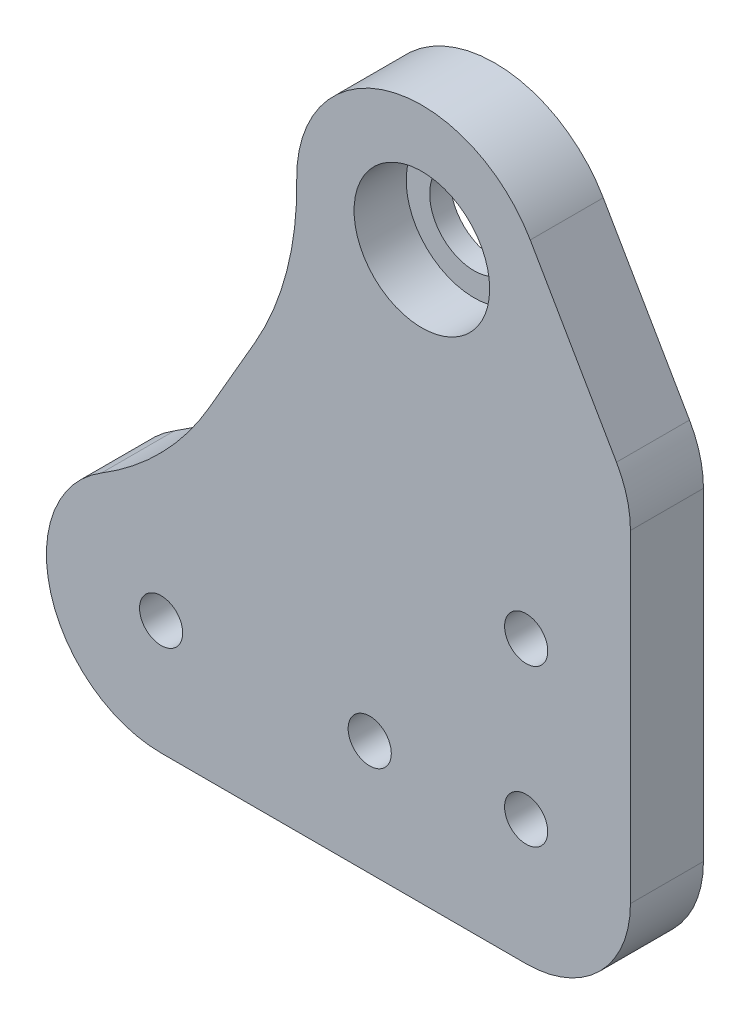
SolidWorks part; units mm, degrees
ref_plane "前视基准面" through (0, 0, 0) normal (0, 0, 1) x (1, 0, 0)
ref_plane "上视基准面" through (0, 0, 0) normal (0, 1, 0) x (1, 0, 0)
ref_plane "右视基准面" through (0, 0, 0) normal (1, 0, 0) x (0, 0, -1)
sketch "草图1" plane through (0, 0, 0) normal (0, 0, 1) x (1, 0, 0)
  line B0 (8.9872, 27.5663) -> (4.6146, 19.9926)
  line B1 (0, -11) -> (35, -11)
  line B2 (43.6603, 34.9808) -> (35.3923, 49.3013)
  line B3 (45, 29.9808) -> (45, -1)
  circle B4 centre (0, 0) radius 2.07
  circle B5 centre (25, 43.3013) radius 4.25
  arc B6 (25, 55.3013) -> (13.0018, 43.0913) centre (25, 43.3013) ccw
  arc B7 (-5.7324, 9.3883) -> (0, -11) centre (0, 0) ccw
  arc B8 (8.9872, 27.5663) -> (13.0018, 43.0913) centre (-16.9936, 42.5663) ccw
  arc B9 (-5.7324, 9.3883) -> (4.6146, 19.9926) centre (-21.3662, 34.9926) ccw
  circle B10 centre (35, 1) radius 2.07
  circle B11 centre (35, 16) radius 2.07
  arc B12 (35, -11) -> (45, -1) centre (35, -1) ccw
  arc B13 (35.3923, 49.3013) -> (13.0018, 43.0913) centre (25, 43.3013) ccw
  arc B14 (45, 29.9808) -> (43.6603, 34.9808) centre (35, 29.9808) ccw
sketch_block_instance "miscParts6_0-1"
sketch_block "miscParts6_0"
extrude "凸台-拉伸1" add sketch "草图1" along normal blind 7 contours B3 B14 B2 B13 B6 B8 B0 B9 B7 B1 B12 B4 B5 B10 B11
sketch "草图2" plane through (0, 0, 7) normal (0, 0, 1) x (1, 0, 0)
  circle A0 centre (25, 43.3013) radius 6.5
  dimension "D1" = 13
extrude "切除-拉伸1" cut sketch "草图2" against normal blind 5
sketch "草图3" plane through (0, 0, 7) normal (0, 0, 1) x (1, 0, 0)
  circle A0 centre (20, 0) radius 2.07
  circle A1 centre (0, 0) radius 2.07 construction
  dimension "D1" = 20
extrude "切除-拉伸2" cut sketch "草图3" against normal through all
